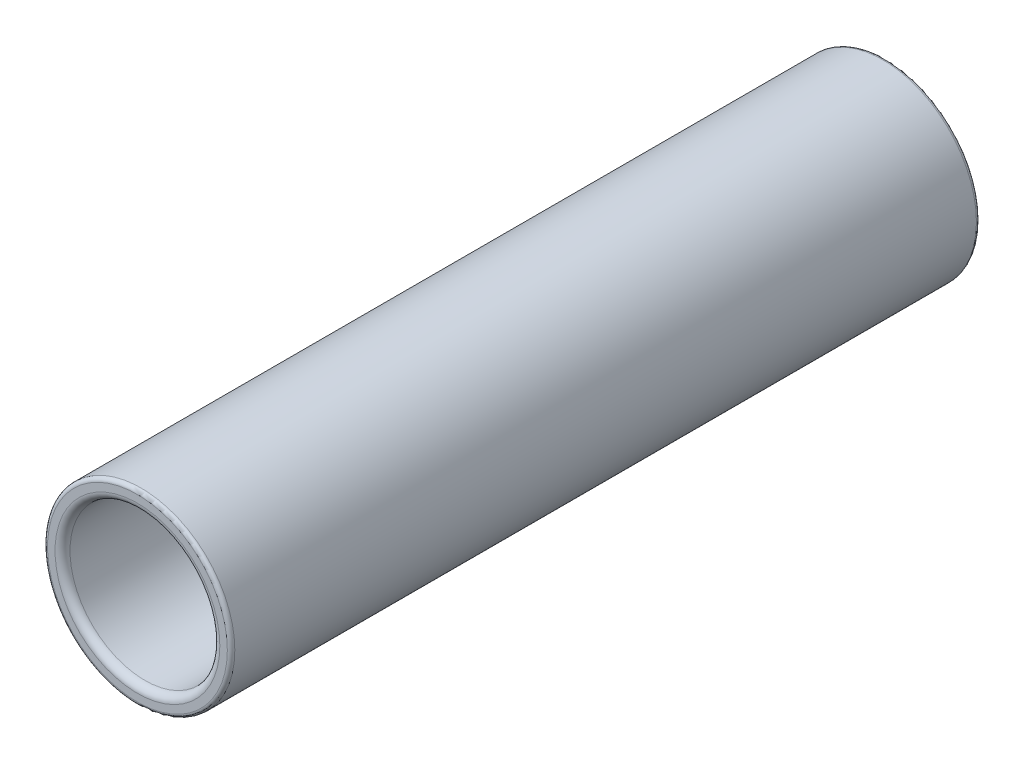
SolidWorks part; units mm, degrees
ref_plane "Alzado" through (0, 0, 0) normal (0, 0, 1) x (1, 0, 0)
ref_plane "Planta" through (0, 0, 0) normal (0, 1, 0) x (1, 0, 0)
ref_plane "Vista lateral" through (0, 0, 0) normal (1, 0, 0) x (0, 0, -1)
sketch "Croquis1" plane through (0, 0, 0) normal (0, 0, 1) x (1, 0, 0)
  circle A0 centre (0, 0) radius 2
  circle A1 centre (0, 0) radius 2.5
  dimension "D1" = 4
  dimension "D2" = 5
extrude "Saliente-Extruir2" add sketch "Croquis1" along normal blind 20
fillet "Redondeo5" radius 0.1 2 edges at (2.5, 0, 0) (2.5, 0, 20)
fillet "Redondeo6" radius 0.2 2 edges at (2, 0, 0) (2, 0, 20)
